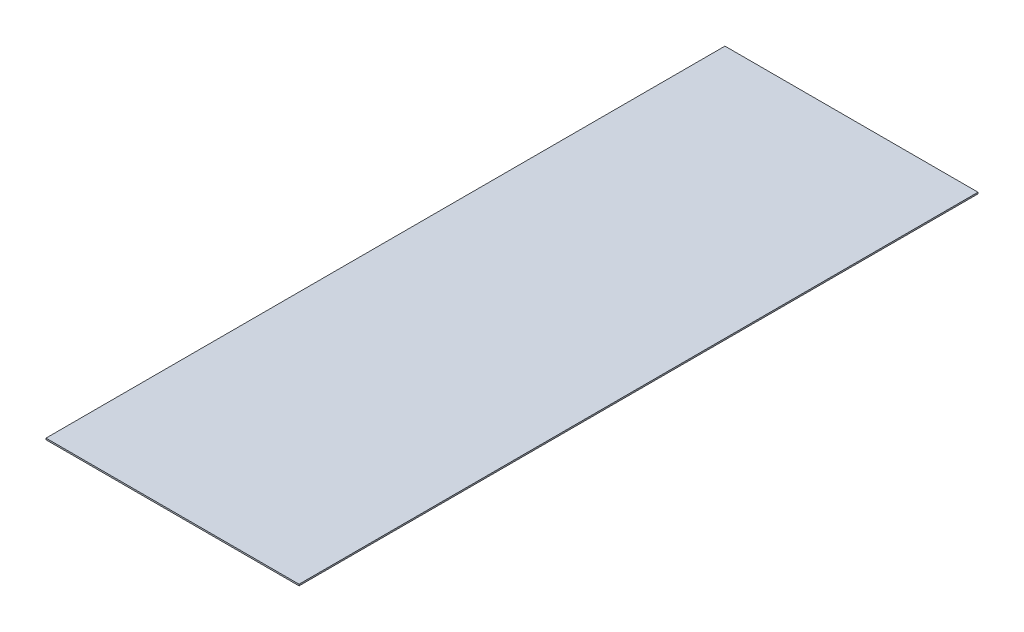
SolidWorks part; units mm, degrees
ref_plane "Front Plane" through (0, 0, 0) normal (0, 0, 1) x (1, 0, 0)
ref_plane "Top Plane" through (0, 0, 0) normal (0, 1, 0) x (1, 0, 0)
ref_plane "Right Plane" through (0, 0, 0) normal (1, 0, 0) x (0, 0, -1)
sketch "Sketch1" plane through (0, 0, 0) normal (0, 1, 0) x (1, 0, 0)
  line L1 (0, 0) -> (2171.7, 0)
  line L2 (0, 0) -> (0, 5826.76)
  line L3 (0, 5826.76) -> (2171.7, 5826.76)
  line L4 (2171.7, 0) -> (2171.7, 5826.76)
  dimension "D1" = 5826.76
  dimension "D2" = 2171.7
extrude "Boss-Extrude1" add sketch "Sketch1" along normal blind 12.7
